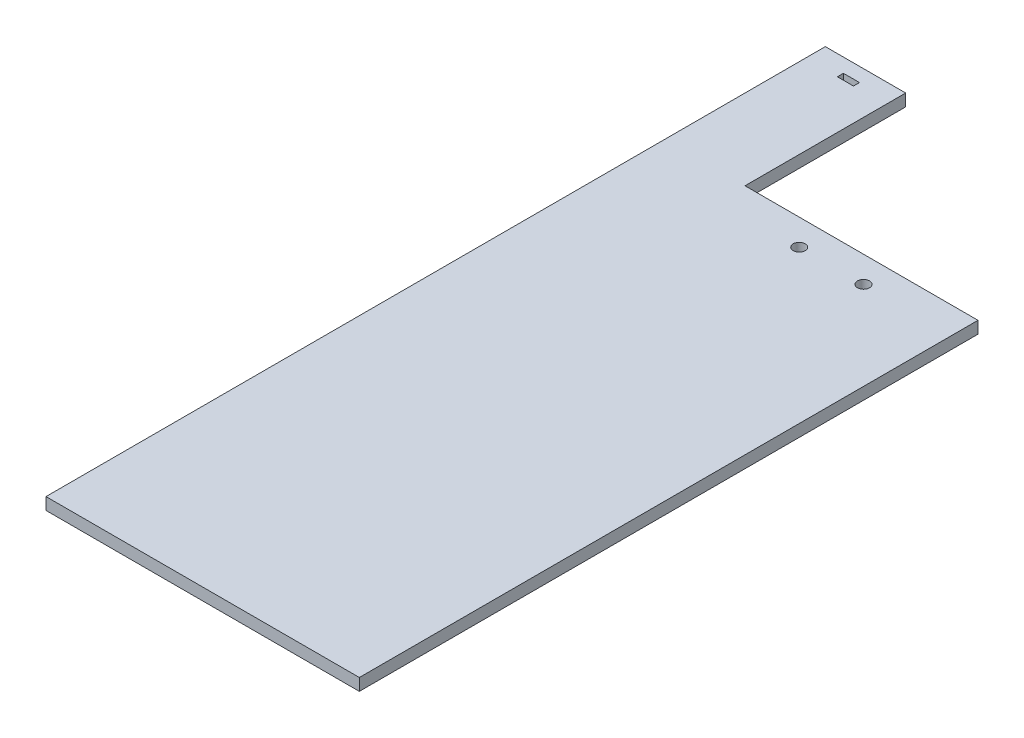
SolidWorks part; units mm, degrees
ref_plane "Front Plane" through (0, 0, 0) normal (0, 0, 1) x (1, 0, 0)
ref_plane "Top Plane" through (0, 0, 0) normal (0, 1, 0) x (1, 0, 0)
ref_plane "Right Plane" through (0, 0, 0) normal (1, 0, 0) x (0, 0, -1)
sketch "Sketch1" plane through (0, 0, 0) normal (0, 1, 0) x (1, 0, 0)
  line L0 (0, 154) -> (0, 194)
  line L1 (0, 0) -> (90, 0)
  line L2 (0, 0) -> (0, 154)
  line L4 (90, 0) -> (90, 154)
  line L5 (0, 194) -> (20, 194)
  line L7 (20, 194) -> (20, 154)
  line L8 (20, 154) -> (90, 154)
  line L10 (8, 190.5) -> (12, 190.5)
  line L11 (8, 190.5) -> (8, 189)
  line L12 (8, 189) -> (12, 189)
  line L13 (12, 190.5) -> (12, 189)
  dimension "D1" = 90
  dimension "D2" = 154
  dimension "D3" = 40
  dimension "D4" = 20
  dimension "D9" = 1.5
  dimension "D10" = 4
  dimension "D11" = 35
  dimension "D12" = 8
extrude "Boss-Extrude1" add sketch "Sketch1" along normal blind 3
sketch "Sketch3" [suppressed] plane through (0, 0, 0) normal (0, 0, 1) x (1, 0, 0)
  line L0 (0, 3) -> (90, 3) construction
  line L1 (90, 0) -> (81, 0)
  line L2 (90, 0) -> (90, 3)
  line L3 (90, 3) -> (81, 3)
  line L4 (81, 0) -> (81, 3)
  dimension "D1" = 9
extrude "Cut-Extrude2" [suppressed] cut sketch "Sketch3" against normal through all
sketch "Sketch4" [suppressed] plane through (0, 0, 0) normal (0, 0, 1) x (1, 0, 0)
  line L0 (0, 3) -> (90, 3) construction
  line L1 (90, 0) -> (86, 0)
  line L2 (90, 0) -> (90, 3)
  line L3 (90, 3) -> (86, 3)
  line L4 (86, 0) -> (86, 3)
  dimension "D1" = 4
extrude "Cut-Extrude3" [suppressed] cut sketch "Sketch4" against normal through all
sketch "Sketch5" [suppressed] plane through (0, 0, 0) normal (-1, 0, 0) x (0, 0, 1)
  line L0 (-194, 3) -> (0, 3) construction
  line L1 (0, 0) -> (-39, 0)
  line L2 (0, 0) -> (0, 3)
  line L3 (0, 3) -> (-39, 3)
  line L4 (-39, 0) -> (-39, 3)
  dimension "D1" = 39
extrude "Cut-Extrude4" [suppressed] cut sketch "Sketch5" against normal through all
sketch "Sketch6" plane through (0, 0, 0) normal (0, 0, 1) x (1, 0, 0)
  line L0 (0, 3) -> (90, 3) construction
  line L1 (90, 0) -> (78, 0)
  line L2 (90, 0) -> (90, 3)
  line L3 (90, 3) -> (78, 3)
  line L4 (78, 0) -> (78, 3)
  dimension "D1" = 12
extrude "Cut-Extrude5" cut sketch "Sketch6" against normal through all
sketch "Sketch7" [suppressed] plane through (0, 3, 0) normal (0, 1, 0) x (1, 0, 0)
  line L1 (42.5, 147.5) -> (58.5, 147.5) construction
  line L2 (81, 154) -> (81, 0) construction
  line L3 (81, 154) -> (20, 154) construction
  circle A0 centre (42.5, 147.5) radius 1.5
  circle A1 centre (58.5, 147.5) radius 1.5
  point P6 (50.5, 147.5)
  dimension "D1" = 3
  dimension "D2" = 3
  dimension "D3" = 16
  dimension "D4" = 30.5
  dimension "D5" = 6.5
sketch "Sketch8" [suppressed] plane through (0, 3, 0) normal (0, 1, 0) x (1, 0, 0)
  line L0 (45, 147.5) -> (61, 147.5) construction
  line L1 (86, 154) -> (20, 154) construction
  line L2 (86, 154) -> (86, 39) construction
  circle A0 centre (45, 147.5) radius 1.5
  circle A1 centre (61, 147.5) radius 1.5
  point P6 (53, 154)
  point P7 (53, 147.5)
  dimension "D1" = 3
  dimension "D2" = 3
  dimension "D3" = 16
  dimension "D4" = 6.5
  dimension "D5" = 33
sketch "Sketch9" [suppressed] plane through (0, 3, 0) normal (0, 1, 0) x (1, 0, 0)
  line L0 (47, 147.5) -> (63, 147.5) construction
  line L3 (90, 39) -> (90, 154) construction
  line L4 (90, 154) -> (20, 154) construction
  circle A0 centre (47, 147.5) radius 1.5
  circle A1 centre (63, 147.5) radius 1.5
  point P4 (55, 147.5)
  dimension "D1" = 3
  dimension "D2" = 3
  dimension "D3" = 16
  dimension "D4" = 35
  dimension "D5" = 6.5
sketch "Sketch10" plane through (0, 3, 0) normal (0, 1, 0) x (1, 0, 0)
  line L0 (40, 147.5) -> (56, 147.5) construction
  line L1 (78, 154) -> (20, 154) construction
  line L2 (78, 154) -> (78, 0) construction
  circle A0 centre (40, 147.5) radius 1.5
  circle A1 centre (56, 147.5) radius 1.5
  point P6 (48, 147.5)
  dimension "D1" = 3
  dimension "D2" = 3
  dimension "D3" = 16
  dimension "D4" = 6.5
  dimension "D5" = 30
extrude "Cut-Extrude6" [suppressed] cut sketch "Sketch7" against normal blind 10
extrude "Cut-Extrude7" [suppressed] cut sketch "Sketch8" against normal blind 10
extrude "Cut-Extrude8" [suppressed] cut sketch "Sketch9" against normal blind 10
extrude "Cut-Extrude9" cut sketch "Sketch10" against normal blind 10
